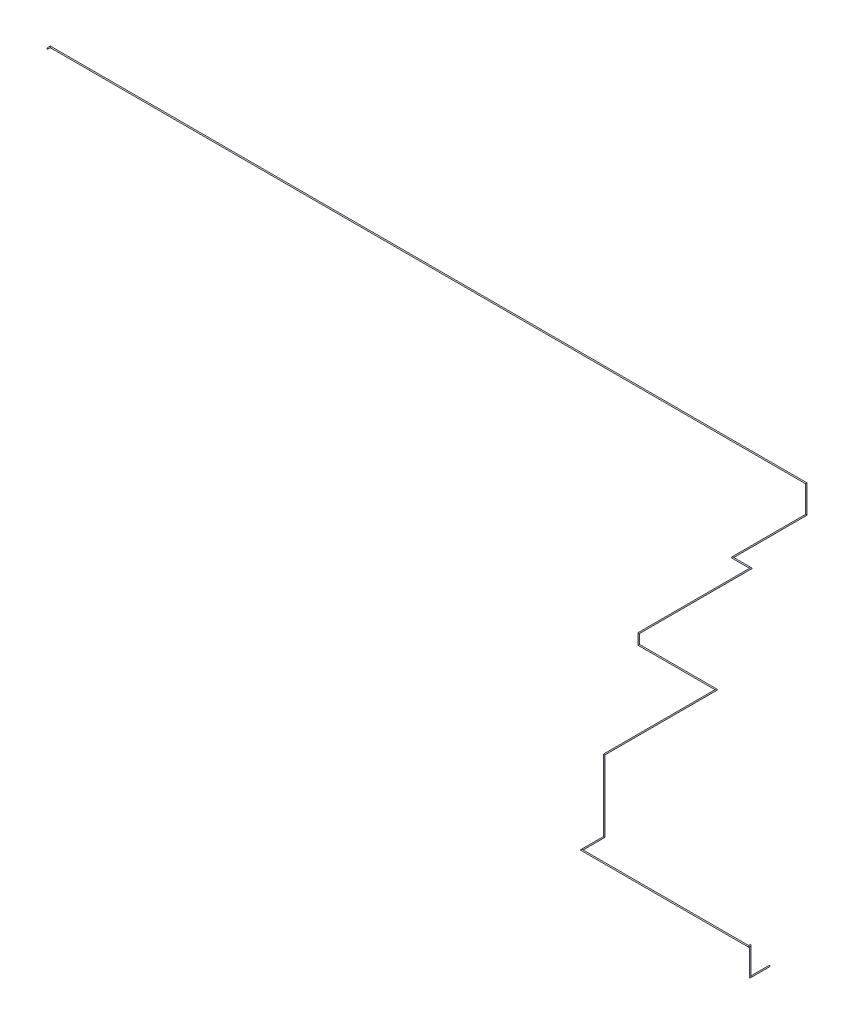
SolidWorks part; units mm, degrees
ref_plane "Alzado" through (0, 0, 0) normal (0, 0, 1) x (1, 0, 0)
ref_plane "Planta" through (0, 0, 0) normal (0, 1, 0) x (1, 0, 0)
ref_plane "Vista lateral" through (0, 0, 0) normal (1, 0, 0) x (0, 0, -1)
sketch "Croquis1" plane through (0, 0, 0) normal (0, 0, 1) x (1, 0, 0)
  circle A0 centre (0, 0) radius 19.05
  dimension "D1" = 38.1
extrude "Saliente-Extruir1" add sketch "Croquis1" along normal blind 10
sketch3d "Croquis3D1"
  line L0 (0, 0, 10) -> (0, 0, 660)
  line L1 (0, 0, 10) -> (0, 0, 0) construction
  line L2 (0, 0, 660) -> (0, 950, 660)
  line L3 (0, 950, 660) -> (0, 950, 720)
  line L4 (0, 950, 720) -> (-5800, 950, 720)
  line L5 (-5800, 950, 720) -> (-5800, 950, -60)
  line L6 (-5800, 950, -60) -> (-5800, 3430, -60)
  line L7 (-5800, 3430, -60) -> (-5800, 3430, -3960)
  line L8 (-5800, 3430, -3960) -> (-8500, 3430, -3960)
  line L9 (-8500, 3430, -3960) -> (-8500, 3780, -3960)
  line L10 (-8500, 3780, -3960) -> (-8500, 3780, -7860)
  line L11 (-8500, 3780, -7860) -> (-9150, 3780, -7860)
  line L12 (-9150, 3780, -7860) -> (-9150, 3780, -10430)
  line L13 (-9150, 3780, -10430) -> (-9150, 4725, -10430)
  line L14 (-9150, 4725, -10430) -> (-35400, 4725, -10430)
  line L15 (-35400, 4725, -10430) -> (-35400, 4725, -10330)
  dimension "D1" = 650
  dimension "D2" = 950
  dimension "D3" = 60
  dimension "D4" = 5800
  dimension "D5" = 780
  dimension "D13" = 945
  dimension "D6" = 2480
  dimension "D7" = 3900
  dimension "D8" = 2700
  dimension "D9" = 350
  dimension "D10" = 3900
  dimension "D11" = 650
  dimension "D12" = 2570
  dimension "D14" = 26250
  dimension "D15" = 100
sketch "Croquis2" plane through (0, 0, 10) normal (0, 0, 1) x (1, 0, 0)
  circle A0 centre (0, 0) radius 19.05
  dimension "D1" = 38.1
sweep "Barrer1" add profiles "Croquis2" path "Croquis3D1"
sketch "Croquis3" plane through (0, 0, 0) normal (0, 0, -1) x (-1, 0, 0)
  line L1 (-19.1903, -0.1269) -> (-18.9097, -0.1269)
  line L2 (-19.1903, -0.1269) -> (-19.1903, 0.1269)
  line L3 (-19.1903, 0.1269) -> (-18.9097, 0.1269)
  line L4 (-18.9097, -0.1269) -> (-18.9097, 0.1269)
  line L5 (-19.1903, -0.1269) -> (-18.9097, 0.1269) construction
  line L6 (-19.1903, 0.1269) -> (-18.9097, -0.1269) construction
  circle A0 centre (0, 0) radius 19.05 construction
  point P0 (-19.05, 0)
extrude "Saliente-Extruir2" add sketch "Croquis3" against normal blind 1
